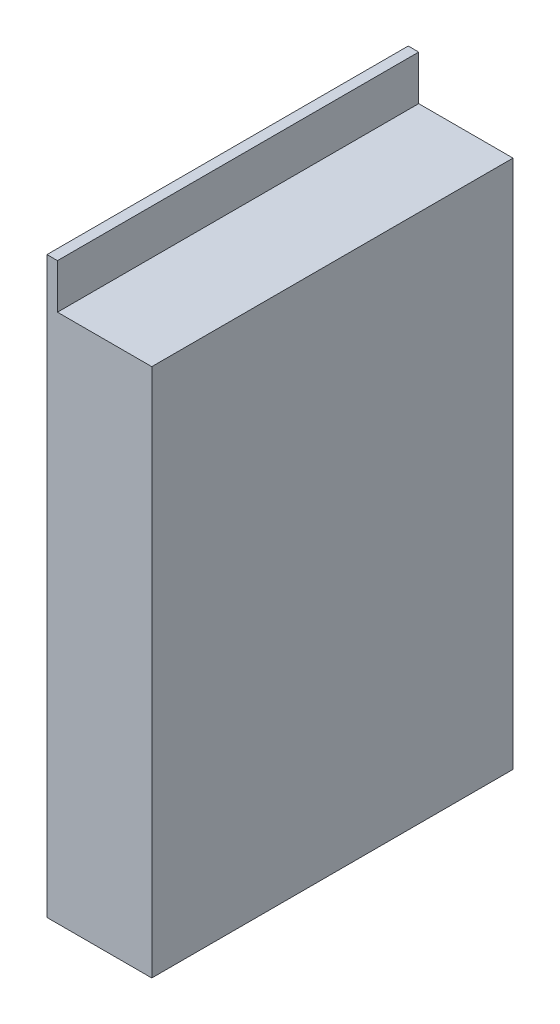
SolidWorks part; units mm, degrees
ref_plane "Front Plane" through (0, 0, 0) normal (0, 0, 1) x (1, 0, 0)
ref_plane "Top Plane" through (0, 0, 0) normal (0, 1, 0) x (1, 0, 0)
ref_plane "Right Plane" through (0, 0, 0) normal (1, 0, 0) x (0, 0, -1)
sketch "Sketch2" plane through (0, 0, 0) normal (1, 0, 0) x (0, 0, -1)
  line L1 (0, 0) -> (65.5, 0)
  line L2 (0, 0) -> (0, 96)
  line L3 (0, 96) -> (65.5, 96)
  line L4 (65.5, 0) -> (65.5, 96)
  dimension "D1" = 96
  dimension "D2" = 65.5
extrude "Boss-Extrude1" add sketch "Sketch2" along normal blind 19
sketch "Sketch3" plane through (0, 96, 0) normal (0, 1, 0) x (1, 0, 0)
  line L1 (0, 65.5) -> (1.9, 65.5)
  line L2 (0, 65.5) -> (0, 0)
  line L3 (0, 0) -> (1.9, 0)
  line L4 (1.9, 65.5) -> (1.9, 0)
  dimension "D1" = 1.9
extrude "Boss-Extrude2" add sketch "Sketch3" along normal blind 8.1
